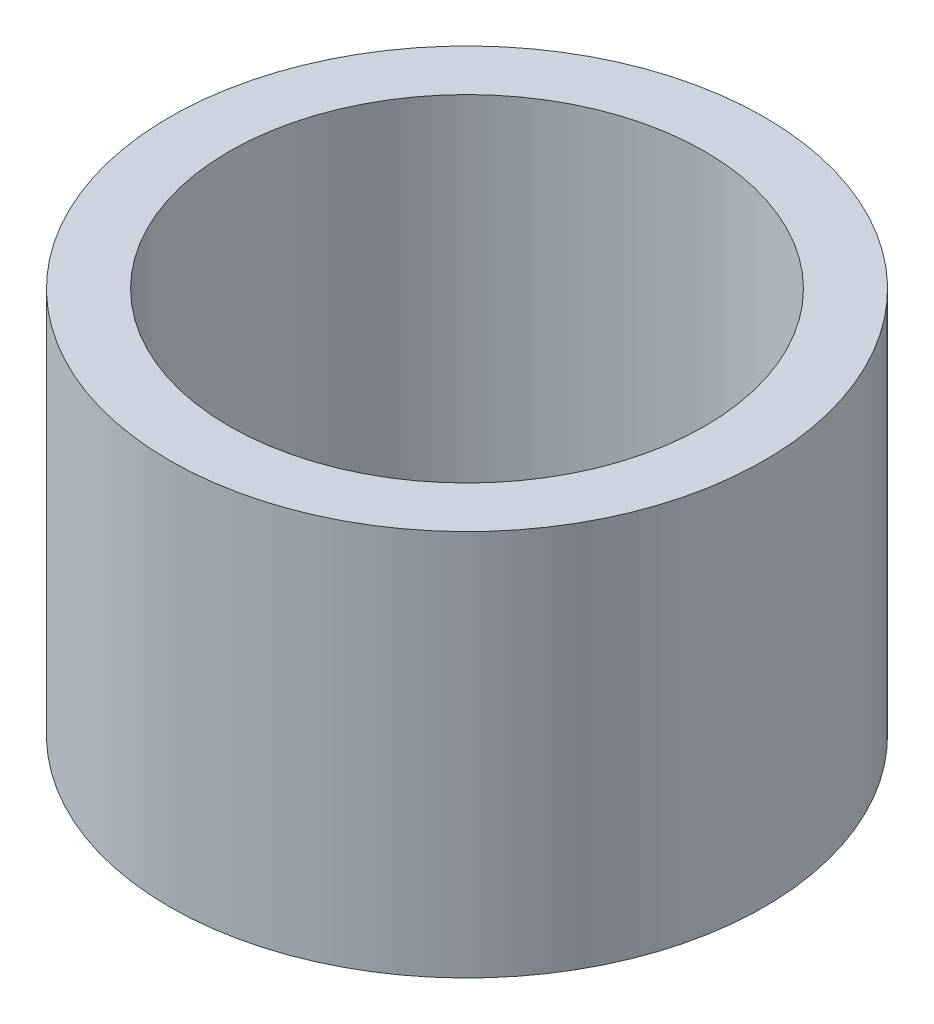
SolidWorks part; units mm, degrees
ref_plane "Front Plane" through (0, 0, 0) normal (0, 0, 1) x (1, 0, 0)
ref_plane "Top Plane" through (0, 0, 0) normal (0, 1, 0) x (1, 0, 0)
ref_plane "Right Plane" through (0, 0, 0) normal (1, 0, 0) x (0, 0, -1)
sketch "Sketch1" plane through (0, 0, 0) normal (0, 1, 0) x (1, 0, 0)
  arc A0 (-8, 0) -> (8, 0) centre (0, 0) cw
  arc A1 (-10, 0) -> (10, 0) centre (0, 0) cw
  circle A2 centre (0, 0) radius 10
  arc A3 (-8, 0) -> (8, 0) centre (0, 0) ccw
  dimension "D1" = 8
  dimension "D2" = 10
  dimension "D3" = 8
  dimension "D4" = 20
extrude "Boss-Extrude1" add sketch "Sketch1" along normal blind 13 contours A2 | A0 A3
